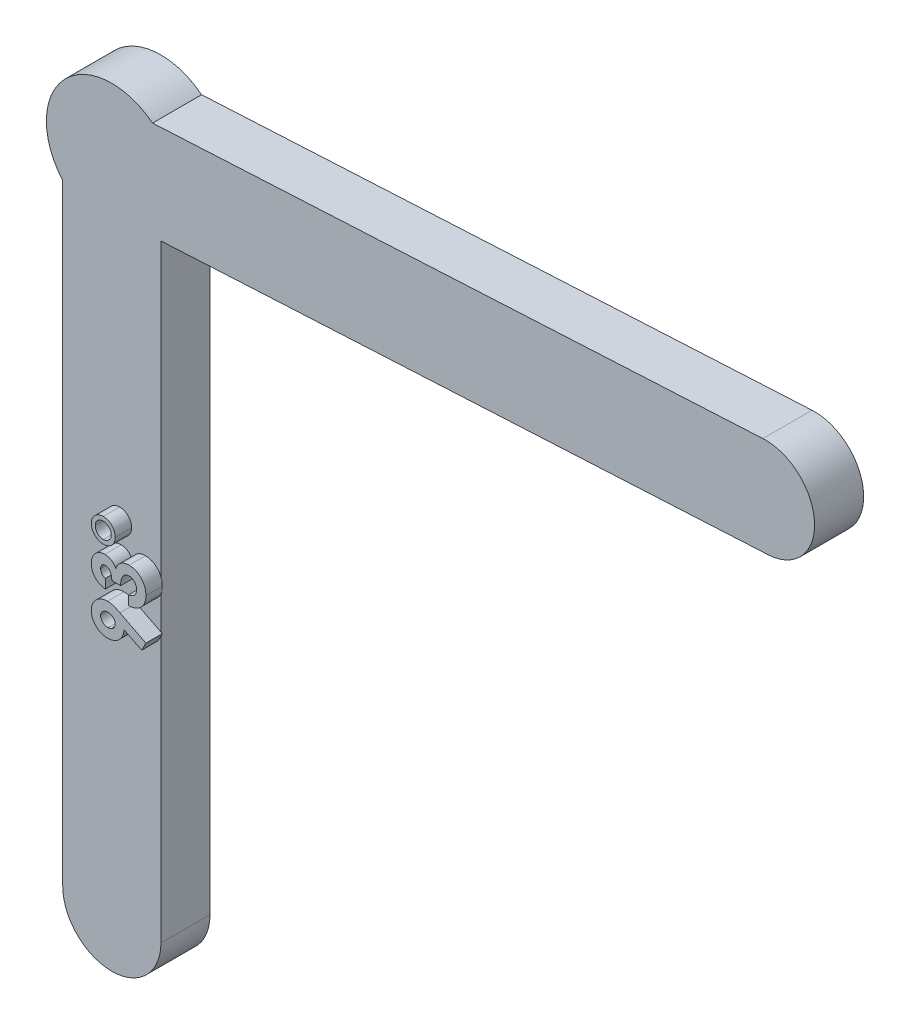
SolidWorks part; units mm, degrees
ref_plane "Front Plane" through (0, 0, 0) normal (0, 0, 1) x (1, 0, 0)
ref_plane "Top Plane" through (0, 0, 0) normal (0, 1, 0) x (1, 0, 0)
ref_plane "Right Plane" through (0, 0, 0) normal (1, 0, 0) x (0, 0, -1)
sketch "Sketch2" plane through (0, 0, 0) normal (0, 0, 1) x (1, 0, 0)
  line L0 (0, 0) -> (0, -40) construction
  line L1 (0, 0) -> (39.9452, 2.0934) construction
  line L2 (39.7882, 5.0893) -> (40.1022, -0.9025) construction
  line L3 (-3, -40) -> (3, -40) construction
  line L4 (-3, -40) -> (-3, -2.6458)
  line L5 (3, -40) -> (3, -2.8469)
  line L6 (39.7882, 5.0893) -> (2.4851, 3.1344)
  line L7 (40.1022, -0.9025) -> (3, -2.8469)
  arc A0 (2.4851, 3.1344) -> (-3, -2.6458) centre (0, 0) ccw
  arc A1 (-3, -40) -> (3, -40) centre (0, -40) ccw
  arc A2 (39.7882, 5.0893) -> (40.1022, -0.9025) centre (39.9452, 2.0934) cw
  point P12 (39.9452, 2.0934)
  dimension "D3" = 3
  dimension "D4" = 8
  dimension "D1" = 40
  dimension "D2" = 93
extrude "Boss-Extrude1" add sketch "Sketch2" along normal blind 3
sketch "Sketch3" plane through (0, 0, 3) normal (0, 0, 1) x (1, 0, 0)
  text T0 "<b>93°</b>"
extrude "Boss-Extrude2" add sketch "Sketch3" along normal blind 1
